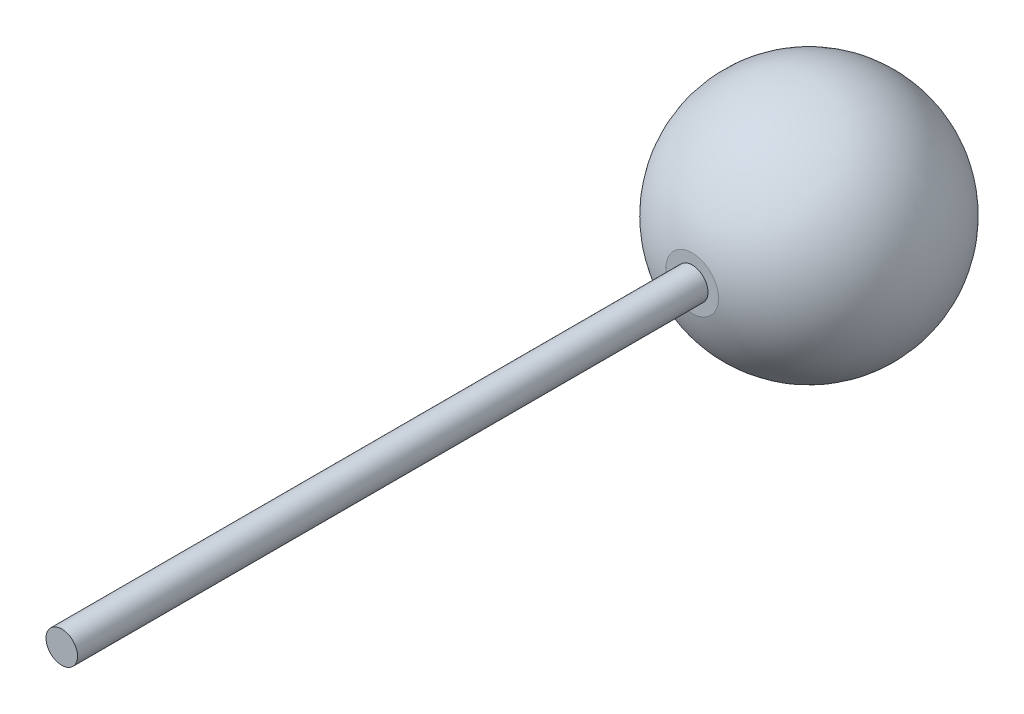
SolidWorks part; units mm, degrees
ref_plane "Front Plane" through (0, 0, 0) normal (0, 0, 1) x (1, 0, 0)
ref_plane "Top Plane" through (0, 0, 0) normal (0, 1, 0) x (1, 0, 0)
ref_plane "Right Plane" through (0, 0, 0) normal (1, 0, 0) x (0, 0, -1)
sketch "Sketch5" plane through (0, 0, 0) normal (0, 1, 0) x (1, 0, 0)
  line L0 (0, 0) -> (1.27, 0)
  line L1 (0, 11.43) -> (0, 0)
  line L2 (0, 5.4606) -> (0, -0.7873) construction
  arc A0 (1.27, 0) -> (0, 11.43) centre (-0.0005, 5.6444) ccw
  dimension "D3" = 5.7856
  dimension "D1" = 1.27
  dimension "D2" = 11.43
revolve "Revolve9" add sketch "Sketch5" angle 360 about L2
sketch "Sketch7" plane through (0, 0, 0) normal (0, 0, 1) x (1, 0, 0)
  circle A0 centre (0, 0) radius 0.762
  dimension "D1" = 1.524
extrude "Boss-Extrude2" add sketch "Sketch7" along normal blind 30.48
